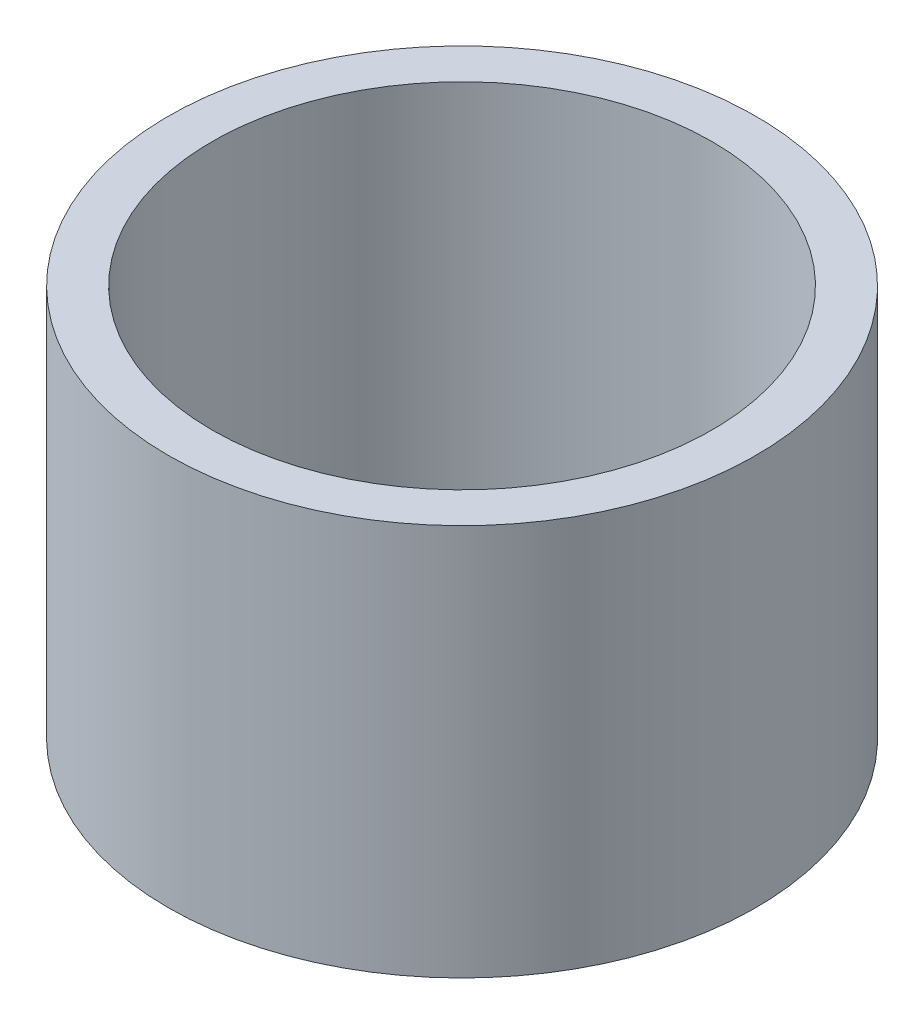
SolidWorks part; units mm, degrees
ref_plane "Front Plane" through (0, 0, 0) normal (0, 0, 1) x (1, 0, 0)
ref_plane "Top Plane" through (0, 0, 0) normal (0, 1, 0) x (1, 0, 0)
ref_plane "Right Plane" through (0, 0, 0) normal (1, 0, 0) x (0, 0, -1)
sketch "Sketch1" plane through (0, 0, 0) normal (0, 1, 0) x (1, 0, 0)
  circle A0 centre (0, 0) radius 4.7625
  circle A1 centre (0, 0) radius 4.0513
  point P5 (0, 0)
  dimension "D1" = 8.1026
  dimension ".375" = 9.525
extrude "Boss-Extrude1" add sketch "Sketch1" along normal blind 6.35
